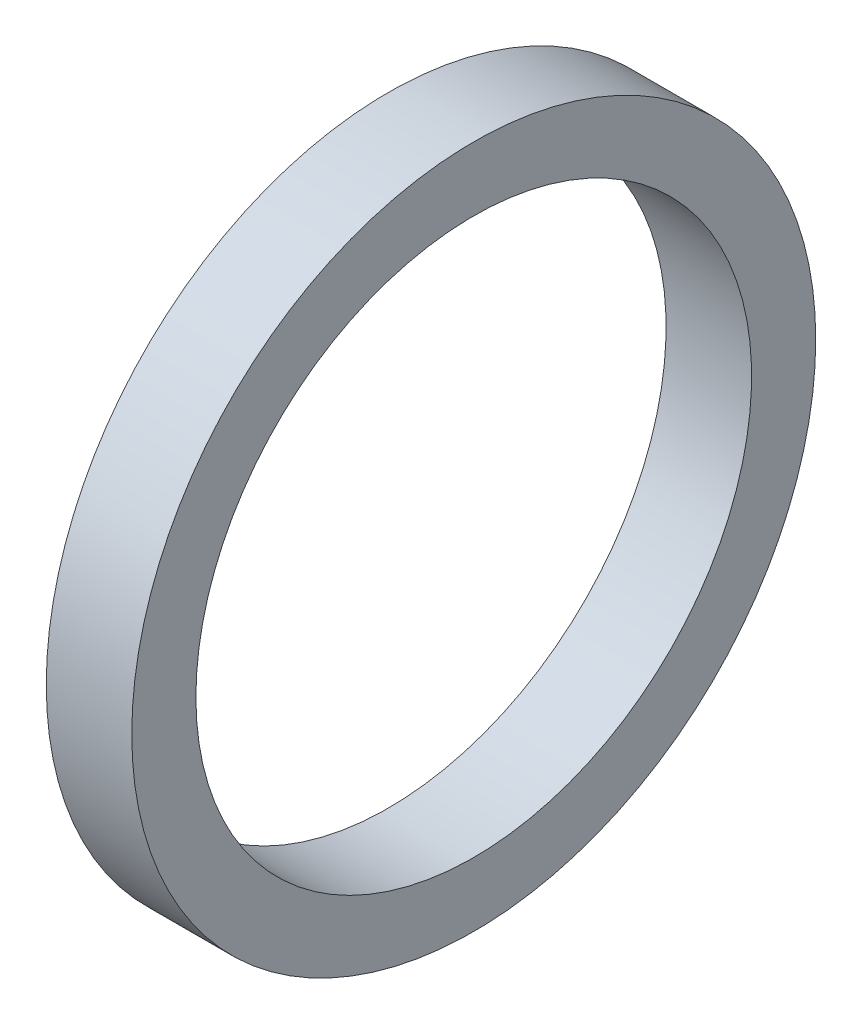
SolidWorks part; units mm, degrees
ref_plane "前视基准面" through (0, 0, 0) normal (0, 0, 1) x (1, 0, 0)
ref_plane "上视基准面" through (0, 0, 0) normal (0, 1, 0) x (1, 0, 0)
ref_plane "右视基准面" through (0, 0, 0) normal (1, 0, 0) x (0, 0, -1)
other "Configuration Table"
sketch "草图1" plane through (0, 0, 0) normal (0, 0, 1) x (1, 0, 0)
  line L0 (-59.6593, 0) -> (89.3294, 0) construction
  line L1 (0, 0) -> (0, 32.5)
  line L2 (0, 32.5) -> (10, 32.5)
  line L3 (10, 32.5) -> (10, 40)
  line L4 (10, 40) -> (0, 40)
  line L5 (0, 40) -> (0, 32.5)
  dimension "D1" = 32.5
  dimension "D2" = 7.5
  dimension "D3" = 10
revolve "旋转1" add sketch "草图1" angle 360 about L0
